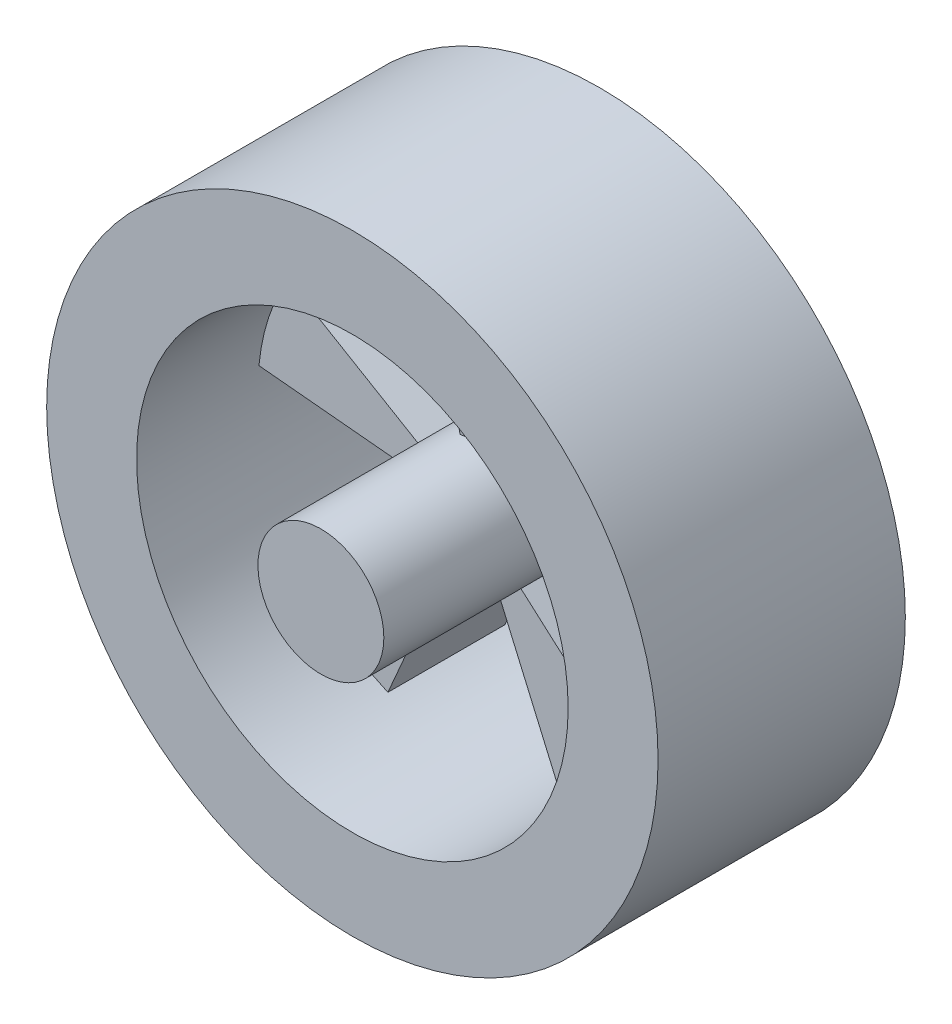
SolidWorks part; units mm, degrees
ref_plane "Alzado" through (0, 0, 0) normal (0, 0, 1) x (1, 0, 0)
ref_plane "Planta" through (0, 0, 0) normal (0, 1, 0) x (1, 0, 0)
ref_plane "Vista lateral" through (0, 0, 0) normal (1, 0, 0) x (0, 0, -1)
sketch "Croquis1" plane through (0, 0, 0) normal (0, 0, 1) x (1, 0, 0)
  circle A1 centre (0, 0) radius 24
  circle A2 centre (0, 0) radius 34
  point P21 (0, 0)
  dimension "D2" = 48
  dimension "D3" = 68
extrude "Saliente-Extruir2" add sketch "Croquis1" along normal blind 26.5 and the other way blind 1 contours A2 A1
sketch "Croquis2" plane through (0, 0, 0) normal (0, 0, 1) x (1, 0, 0)
  circle A0 centre (0, 0) radius 7
extrude "Saliente-Extruir3" add sketch "Croquis2" along normal blind 30 separate body
sketch "Croquis3" plane through (0, 0, 0) normal (0, 0, 1) x (1, 0, 0)
  line L0 (-5.2159, 23.4264) -> (0, 0)
  line L1 (0, 0) -> (5.2159, 23.4264)
  line L2 (20.668, 12.1997) -> (0, 0)
  line L3 (17.9894, -15.8865) -> (0, 0)
  line L4 (-9.55, -22.0181) -> (0, 0)
  line L5 (-23.8916, 2.2786) -> (0, 0)
  line L6 (0, 0) -> (23.8916, 2.2786)
  line L7 (0, 0) -> (9.55, -22.0181)
  line L8 (0, 0) -> (-17.9894, -15.8865)
  line L9 (0, 0) -> (-20.668, 12.1997)
  circle A0 centre (0, 0) radius 24
  point P12 (0, 0)
  point P17 (0, 0)
extrude "Saliente-Extruir4" add sketch "Croquis3" along normal blind 13 contours L1 A0 L0 | L9 A0 L5 | L6 A0 L2 | L7 A0 L3 | L8 A0 L4
